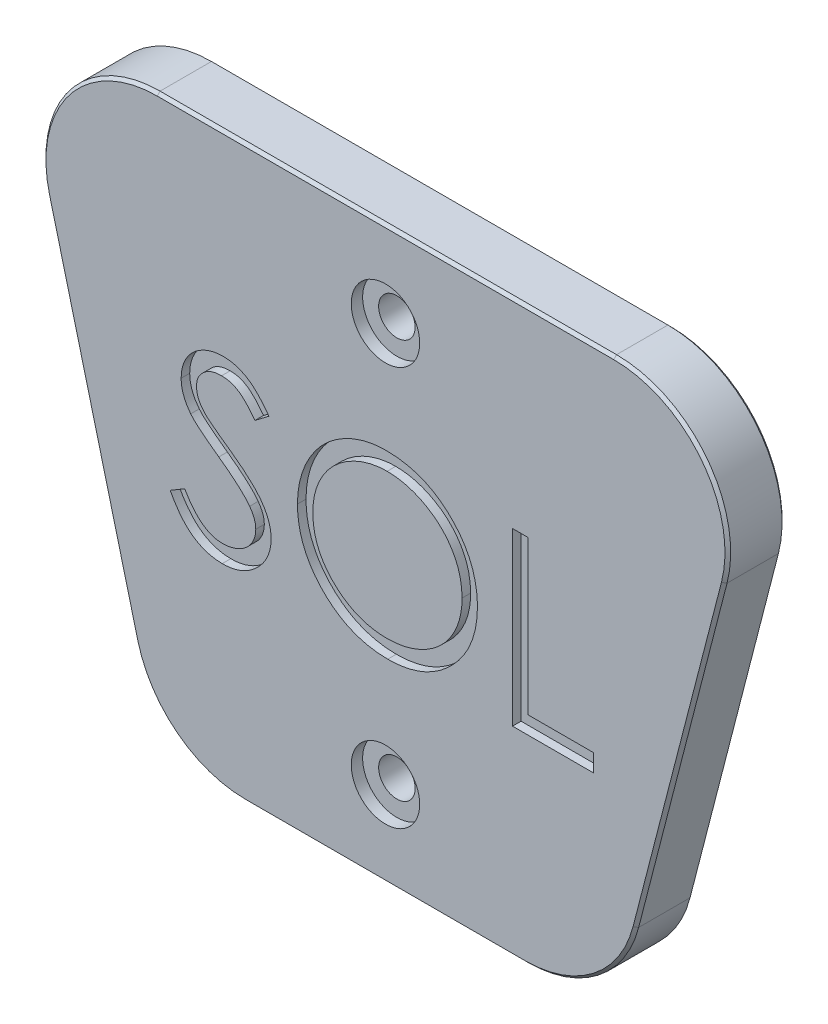
SolidWorks part; units mm, degrees
ref_plane "Front Plane" through (0, 0, 0) normal (0, 0, 1) x (1, 0, 0)
ref_plane "Top Plane" through (0, 0, 0) normal (0, 1, 0) x (1, 0, 0)
ref_plane "Right Plane" through (0, 0, 0) normal (1, 0, 0) x (0, 0, -1)
sketch "Sketch2" plane through (0, 0, 0) normal (0, 0, 1) x (1, 0, 0)
  line L0 (20, -80) -> (100, -80)
  line L6 (100, 20) -> (20, 20)
  line L8 (0.6351, -5) -> (20, -80)
  line L9 (119.3649, -5) -> (100, -80)
  line L10 (120, 23.0116) -> (120, 0)
  line L11 (0, 0) -> (0, 50.4461)
  line L12 (60, 20) -> (60, -80) construction
  arc A4 (119.3649, -5) -> (100, 20) centre (100, 0) ccw
  arc A5 (0.6351, -5) -> (20, 20) centre (20, 0) cw
  point P2 (120, 23.0116)
  point P7 (15.5222, -80)
  point P12 (120, 23.0116)
  point P15 (0, 0)
  point P21 (0, 0)
  dimension "D3" = 20
  dimension "D1" = 120
  dimension "D2" = 100
  dimension "D4" = 80
extrude "Boss-Extrude1" add sketch "Sketch2" along normal blind 10
fillet "Fillet2" radius 20 2 edges at (20, -80, 5) (100, -80, 5)
sketch "Sketch10" plane through (0, 0, 10) normal (0, 0, 1) x (1, 0, 0)
  line L0 (60, 20) -> (60, -10) construction
  line L3 (60, 20) -> (60, -10) construction
  line L4 (60, -50) -> (60, -80) construction
  line L5 (60, 20) -> (60, -10) construction
  line L6 (60, -50) -> (60, -80) construction
  line L7 (100, 20) -> (20, 20) construction
  line L8 (35.4919, -80) -> (84.5081, -80) construction
  circle A1 centre (60, -65) radius 6
  circle A2 centre (60, 5) radius 6
  dimension "D1" = 12
  dimension "D2" = 15
  dimension "D3" = 15
extrude "Cut-Extrude6" cut sketch "Sketch10" against normal blind 2
sketch "Sketch11" plane through (0, 0, 8) normal (0, 0, 1) x (1, 0, 0)
  circle A0 centre (60, 5) radius 3.2
  circle A2 centre (60, -65) radius 3.2
  dimension "D1" = 6.4
extrude "Cut-Extrude7" cut sketch "Sketch11" against normal through all
sketch "Sketch13" plane through (0, 0, 10) normal (0, 0, 1) x (1, 0, 0)
  line L0 (35.4919, -80) -> (84.5081, -80) construction
  text T0 "SOL" font "Century Gothic" height 30
  dimension "D1" = 35
  dimension "D2" = 21.5
extrude "Cut-Extrude8" cut sketch "Sketch13" against normal blind 1.5
chamfer "Chamfer1" distance 0.5 angle 45 18 edges at (115.8114, 12.2474, 0) (115.8114, 12.2474, 10) (4.1886, 12.2474, 0) (4.1886, 12.2474, 10) (8.381, -35, 0) (8.381, -35, 10) (111.619, -35, 10) (111.619, -35, 0) (63.2, -65, 0) (63.2, 5, 0) (60, -80, 10) (60, -80, 0) (60, 20, 0) (60, 20, 10) (96.7555, -75.8114, 10) (96.7555, -75.8114, 0) (23.2445, -75.8114, 10) (23.2445, -75.8114, 0)
